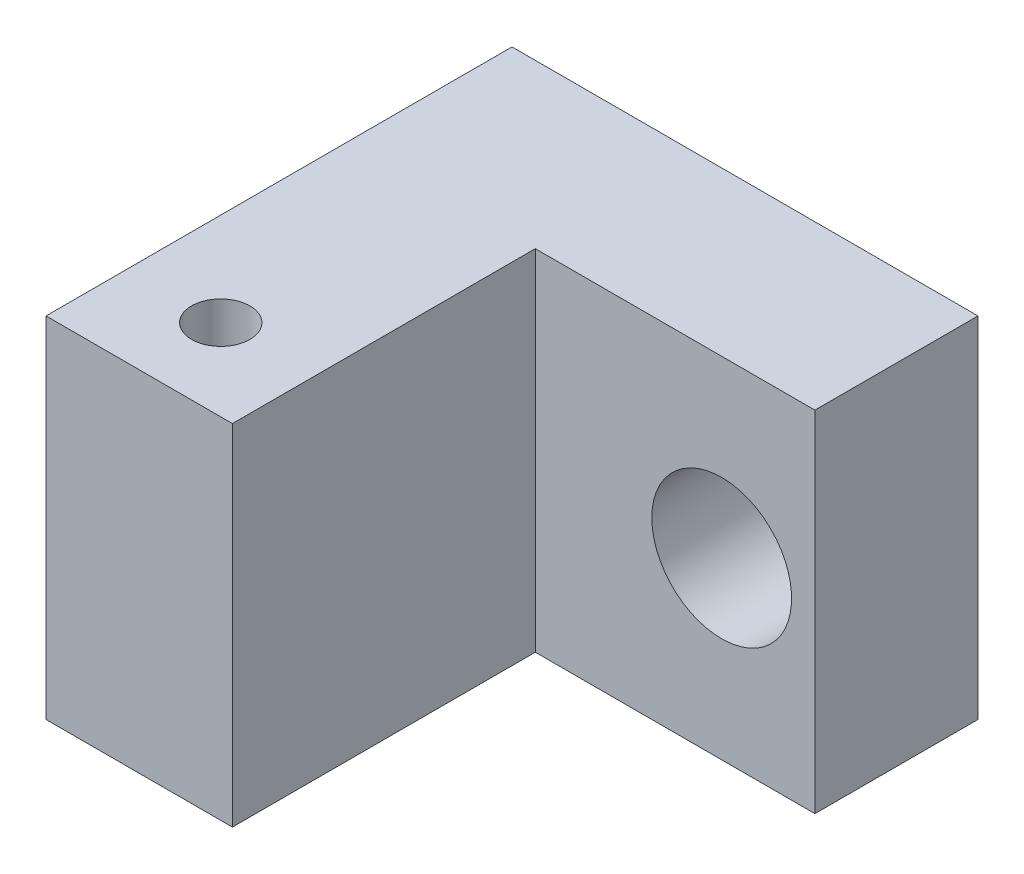
SolidWorks part; units mm, degrees
ref_plane "Piano frontale" through (0, 0, 0) normal (0, 0, 1) x (1, 0, 0)
ref_plane "Piano superiore" through (0, 0, 0) normal (0, 1, 0) x (1, 0, 0)
ref_plane "Piano destro" through (0, 0, 0) normal (1, 0, 0) x (0, 0, -1)
sketch "Schizzo1" plane through (0, 0, 0) normal (0, 1, 0) x (1, 0, 0)
  line L0 (8, -7) -> (20, -7)
  line L1 (0, 0) -> (20, 0)
  line L5 (20, -7) -> (20, 0)
  line L6 (8, -20) -> (8, -7)
  line L7 (0, -20) -> (8, -20)
  line L8 (0, 0) -> (0, -20)
  dimension "D1" = 20
  dimension "D2" = 20
  dimension "D3" = 13
  dimension "D4" = 7
  dimension "D5" = 12
extrude "Estrusione-Estrusione1" add sketch "Schizzo1" along normal blind 15
sketch "Schizzo6" plane through (0, 0, 0) normal (0, 0, -1) x (-1, 0, 0)
  line L0 (-20, 7.5) -> (0, 7.5) construction
  line L1 (-20, 15) -> (-20, 0) construction
  line L2 (0, 15) -> (0, 0) construction
  circle A0 centre (-16, 7.5) radius 3
  dimension "D1" = 6
  dimension "D2" = 4
extrude "Taglio-Estrusione1" cut sketch "Schizzo6" against normal blind 10
sketch "Schizzo7" plane through (0, 15, 0) normal (0, 1, 0) x (1, 0, 0)
  line L0 (4, -20) -> (4, 0) construction
  line L1 (0, -20) -> (8, -20) construction
  line L2 (20, 0) -> (0, 0) construction
  point P6 (4, -16.5)
  dimension "D1" = 3.5
hole_wizard "Foro filettato M3-1" positions "Schizzo3D1" profile "Schizzo8" tap size "M3" standard "ISO" end condition through all
sketch3d "Schizzo3D1"
  point P0 (4, 15, 16.5)
sketch "Schizzo8" plane through (4, 15, 16.5) normal (1, 0, 0) x (0, 0, 1)
  line L0 (0, 0) -> (0, 15)
  line L1 (0, 15) -> (1.25, 15)
  line L2 (1.25, 15) -> (1.25, 0)
  line L5 (1.25, 0) -> (0, 0)
  line L11 (0, -6.35) -> (0, 107.95) construction
  dimension "Thru Tap Drill Dia." = 2.5
  dimension "Thru Tap Drill Depth" = 15
cosmetic thread "Filettatura del foro2" parameters "D2"=3
sketch "CAM" plane through (0, 0, 20) normal (0, 0, 1) x (1, 0, 0)
  line L0 (0, 15) -> (0, 0) construction
  line L1 (7.5, 34.7913) -> (37.8473, 34.7913) construction
  line L2 (7.5, 34.7913) -> (7.5, -16) construction
  line L3 (7.5, -16) -> (37.8473, -16) construction
  line L4 (37.8473, 34.7913) -> (37.8473, -16) construction
  line L5 (0, 0) -> (8, 0) construction
  dimension "D1" = 7.5
  dimension "D2" = 16
